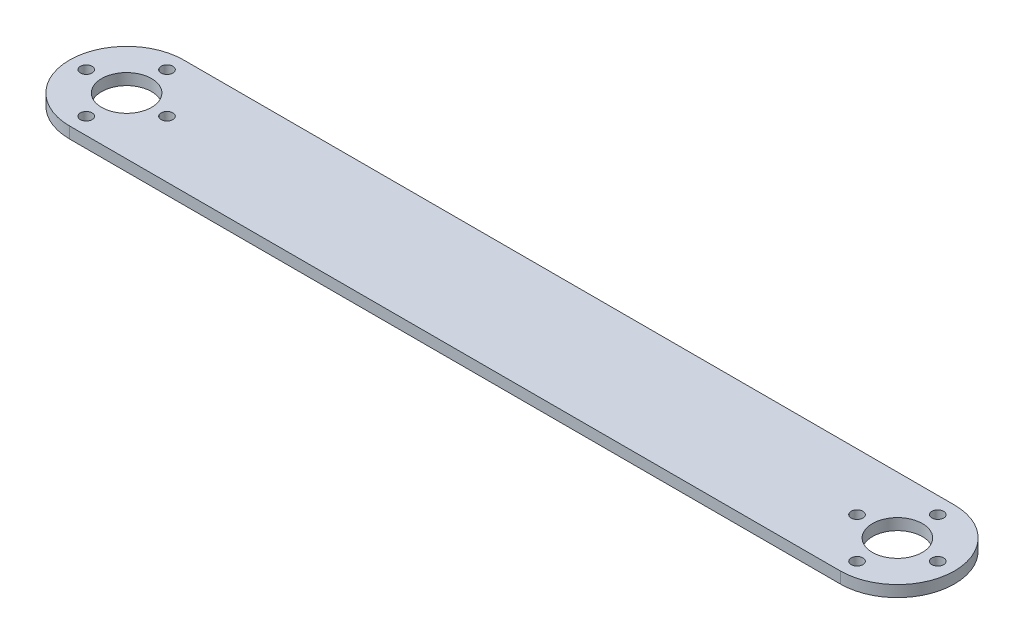
SolidWorks part; units mm, degrees
ref_plane "Front" through (0, 0, 0) normal (0, 0, 1) x (1, 0, 0)
ref_plane "Top" through (0, 0, 0) normal (0, 1, 0) x (1, 0, 0)
ref_plane "Right" through (0, 0, 0) normal (1, 0, 0) x (0, 0, -1)
sketch "Sketch1" plane through (0, 0, 0) normal (0, 1, 0) x (1, 0, 0)
  line L1 (0, 0) -> (216, 0)
  line L2 (0, 0) -> (0, 32)
  line L3 (0, 32) -> (216, 32)
  line L4 (216, 0) -> (216, 32)
  arc A0 (0, 32) -> (0, 0) centre (0, 16) ccw
  arc A1 (216, 32) -> (216, 0) centre (216, 16) cw
  circle A2 centre (0, 16) radius 7
  circle A3 centre (216, 16) radius 7
  dimension "D1" = 32
  dimension "D2" = 216
extrude "Boss-Extrude1" add sketch "Sketch1" along normal blind 3.175 contours A3 L4 L3 L2 A2 L1 | A2 L2 A0 | A3 L4 A1
sketch "Sketch2" plane through (0, 3.175, 0) normal (0, 1, 0) x (1, 0, 0)
  line L0 (108, 32) -> (108, 0)
  line L1 (0, 32) -> (216, 32) construction
  line L2 (0, 0) -> (216, 0) construction
  circle A0 centre (0, 16) radius 11.3137
  circle A1 centre (-11.3137, 16) radius 1.65
  circle A2 centre (11.3137, 16) radius 1.65
  circle A3 centre (0, 27.3137) radius 1.65
  circle A4 centre (0, 4.6863) radius 1.65
  circle A5 centre (216, 4.6863) radius 1.65
  circle A6 centre (204.6863, 16) radius 1.65
  circle A7 centre (227.3137, 16) radius 1.65
  circle A8 centre (216, 27.3137) radius 1.65
  point P25 (0, 0)
  point P26 (0, 0)
extrude "Cut-Extrude1" cut sketch "Sketch2" against normal blind 10 contours A6 | A8 | A1 | A3 | A2 | A4 | A5 | A7
